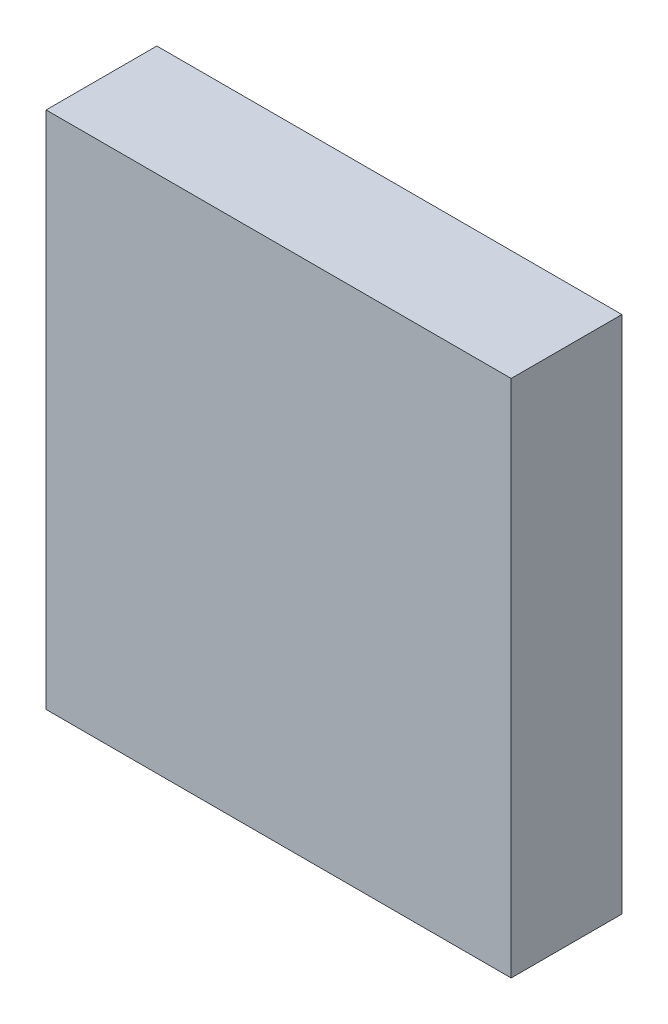
SolidWorks part; units mm, degrees
ref_plane "Front Plane" through (0, 0, 0) normal (0, 0, 1) x (1, 0, 0)
ref_plane "Top Plane" through (0, 0, 0) normal (0, 1, 0) x (1, 0, 0)
ref_plane "Right Plane" through (0, 0, 0) normal (1, 0, 0) x (0, 0, -1)
sketch "Sketch1" plane through (0, 0, 0) normal (0, 0, 1) x (1, 0, 0)
  line L1 (0, 0) -> (273, 0)
  line L2 (0, 0) -> (0, 304.8)
  line L3 (0, 304.8) -> (273, 304.8)
  line L4 (273, 0) -> (273, 304.8)
  dimension "D1" = 273
  dimension "D2" = 304.8
extrude "Boss-Extrude1" add sketch "Sketch1" along normal blind 65
